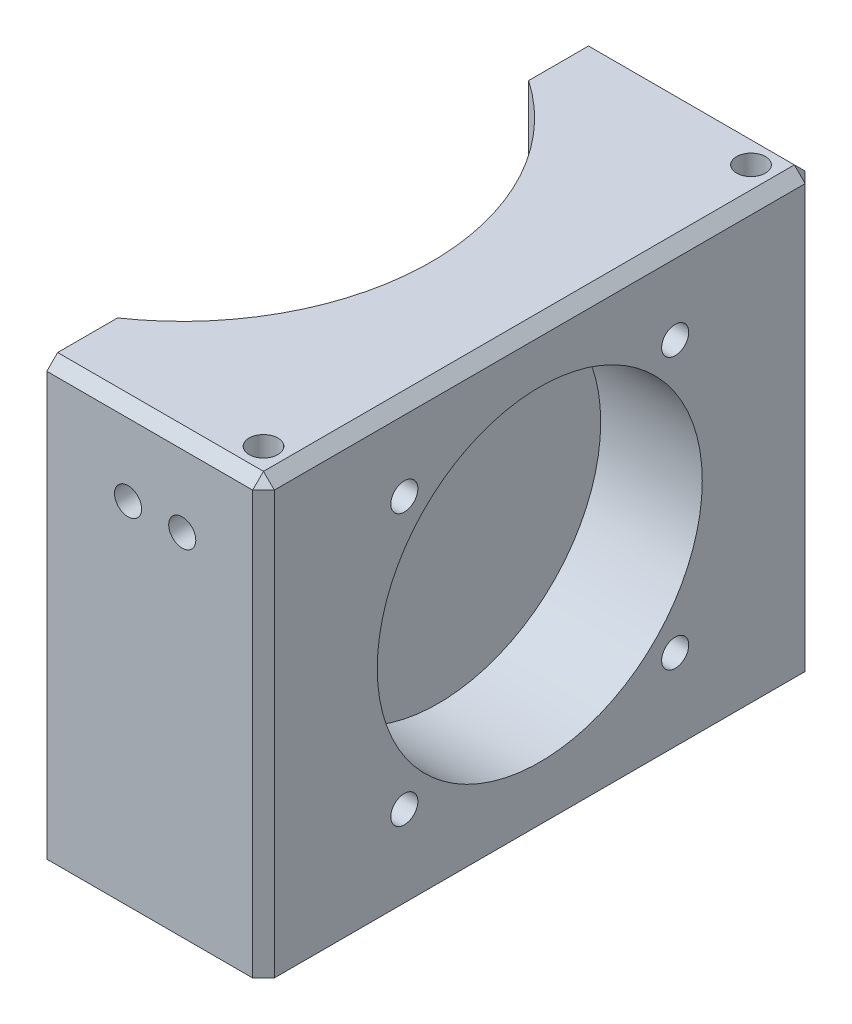
SolidWorks part; units mm, degrees
material "6061-T6 (SS)"
ref_plane "Front Plane" through (0, 0, 0) normal (0, 0, 1) x (1, 0, 0)
ref_plane "Top Plane" through (0, 0, 0) normal (0, 1, 0) x (1, 0, 0)
ref_plane "Right Plane" through (0, 0, 0) normal (1, 0, 0) x (0, 0, -1)
sketch "Sketch1" plane through (0, 0, 0) normal (0, 1, 0) x (1, 0, 0)
  line L0 (33.02, 64.77) -> (33.02, 48.1931)
  line L1 (33.02, -64.77) -> (83.82, -64.77)
  line L2 (33.02, -48.1931) -> (33.02, -64.77)
  line L3 (33.02, 64.77) -> (83.82, 64.77)
  line L4 (83.82, -64.77) -> (83.82, 64.77)
  line L5 (-83.82, -64.77) -> (83.82, 64.77) construction
  line L6 (-83.82, 64.77) -> (83.82, -64.77) construction
  arc A0 (33.02, -48.1931) -> (33.02, 48.1931) centre (0, 0) ccw
  point P0 (0, 0)
  dimension "D1" = 116.84
  dimension "D3" = 64.77
  dimension "D4" = 50.8
extrude "Boss-Extrude1" add sketch "Sketch1" along normal blind 101.6
sketch "Sketch2" plane through (83.82, 0, 0) normal (1, 0, 0) x (0, 0, -1)
  circle A0 centre (0, 50.8) radius 38.1
  dimension "D1" = 76.2
  dimension "D2" = 50.8
extrude "Cut-Extrude2" cut sketch "Sketch2" against normal blind 23.8125
hole_wizard "1/4-20 Tapped Hole1" positions "Sketch4" profile "Sketch5" tap size "1/4-20" standard "Ansi Inch"
sketch "Sketch4" plane through (83.82, 0, 0) normal (1, 0, 0) x (0, 0, -1)
  line L0 (-31.75, 82.55) -> (31.75, 19.05) construction
  line L3 (31.75, 82.55) -> (-31.75, 19.05) construction
  line L6 (0, 0) -> (-31.75, 19.05) construction
  line L9 (31.75, 19.05) -> (0, 0) construction
  line L12 (-64.77, 0) -> (64.77, 0) construction
  point P0 (-31.75, 82.55)
  point P1 (31.75, 82.55)
  point P3 (31.75, 19.05)
  point P5 (-31.75, 19.05)
  dimension "D1" = 63.5
  dimension "D2" = 19.05
sketch "Sketch5" plane through (83.82, 82.55, 31.75) normal (0, 1, 0) x (0, 0, -1)
  line L0 (0, 0) -> (0, 20.5838)
  line L1 (0, 20.5838) -> (2.5527, 19.05)
  line L2 (2.5527, 19.05) -> (2.5527, 12.7)
  line L3 (2.5527, 12.7) -> (3.175, 12.7)
  line L4 (3.175, 12.7) -> (3.175, 0)
  line L5 (3.175, 0) -> (0, 0)
  line L10 (0, 20.5838) -> (-2.5527, 19.05) construction
  line L11 (0, -6.35) -> (0, 107.95) construction
  dimension "Tap Drill Dia." = 5.1054
  dimension "Tap Drill Depth" = 19.05
  dimension "Thread Major Dia." = 6.35
  dimension "Thread Depth" = 12.7
  dimension "Drill Angle" = 118
hole_wizard "H (0.266) Diameter Hole1" positions "Sketch8" profile "Sketch9" hole size "H" standard "Ansi Inch" end condition through all
sketch "Sketch8" plane through (0, 101.6, 0) normal (0, 1, 0) x (-1, 0, 0)
  line L0 (76.2, -57.15) -> (0, 0) construction
  line L1 (0, 0) -> (-76.2, 57.15) construction
  line L4 (-76.2, -57.15) -> (0, 0) construction
  line L5 (0, 0) -> (76.2, 57.15) construction
  point P0 (76.2, -57.15)
  point P1 (76.2, 57.15)
  point P3 (-76.2, 57.15)
  point P5 (-76.2, -57.15)
  dimension "D1" = 152.4
  dimension "D2" = 114.3
sketch "Sketch9" plane through (-76.2, 101.6, -57.15) normal (1, 0, 0) x (0, 0, 1)
  line L0 (0, 0) -> (0, 101.6)
  line L1 (0, 101.6) -> (3.3782, 101.6)
  line L2 (3.3782, 101.6) -> (3.3782, 0)
  line L5 (3.3782, 0) -> (0, 0)
  line L11 (0, -6.35) -> (0, 107.95) construction
  dimension "Thru Hole Dia." = 6.7564
  dimension "Thru Hole Depth" = 101.6
hole_wizard "1/4-20 Tapped Hole2" positions "Sketch12" profile "Sketch11" tap size "1/4-20" standard "Ansi Inch"
sketch "Sketch12" plane through (0, 0, 64.77) normal (0, 0, 1) x (1, 0, 0)
  line L0 (33.02, 101.6) -> (33.02, 0) construction
  point P0 (64.77, 82.2038)
  point P1 (52.07, 82.2038)
  dimension "D1" = 31.75
  dimension "D2" = 19.05
sketch "Sketch11" plane through (64.77, 82.2038, 64.77) normal (1, 0, 0) x (0, -1, 0)
  line L0 (0, 0) -> (0, 20.5838)
  line L1 (0, 20.5838) -> (2.5527, 19.05)
  line L2 (2.5527, 19.05) -> (2.5527, 12.7)
  line L3 (2.5527, 12.7) -> (3.175, 12.7)
  line L4 (3.175, 12.7) -> (3.175, 0)
  line L5 (3.175, 0) -> (0, 0)
  line L10 (0, 20.5838) -> (-2.5527, 19.05) construction
  line L11 (0, -6.35) -> (0, 107.95) construction
  dimension "Tap Drill Dia." = 5.1054
  dimension "Tap Drill Depth" = 19.05
  dimension "Thread Major Dia." = 6.35
  dimension "Thread Depth" = 12.7
  dimension "Drill Angle" = 118
mirror "Mirror1" about plane through (0, 0, 0) normal (0, 0, 1) of "1/4-20 Tapped Hole2"
chamfer "Chamfer1" distance 2.54 angle 45 5 edges at (83.82, 50.8, 64.77) (83.82, 50.8, -64.77) (58.42, 101.6, -64.77) (83.82, 101.6, 0) (58.42, 101.6, 64.77)
